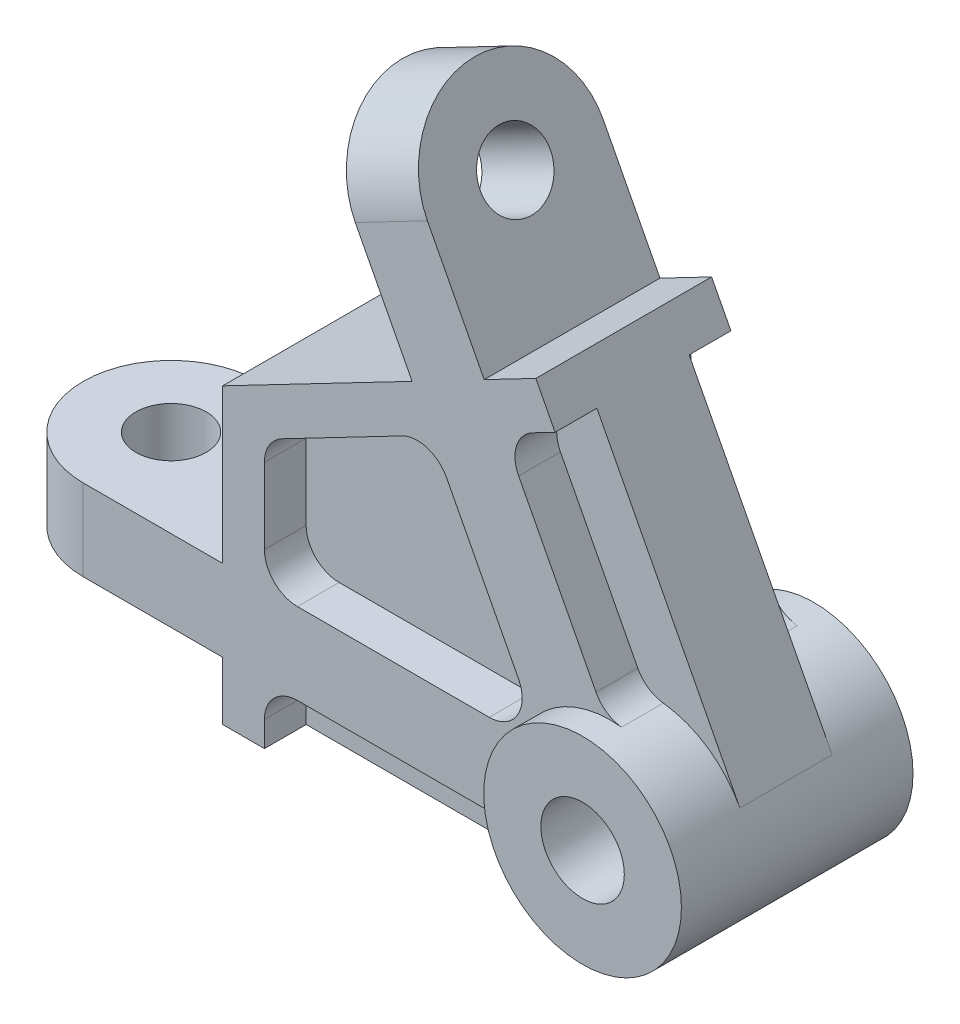
SolidWorks part; units mm, degrees
material "Alliage 1060"
ref_plane "Plan de face" through (0, 0, 0) normal (0, 0, 1) x (1, 0, 0)
ref_plane "Plan de dessus" through (0, 0, 0) normal (0, 1, 0) x (1, 0, 0)
ref_plane "Plan de droite" through (0, 0, 0) normal (1, 0, 0) x (0, 0, -1)
sketch "Esquisse2" plane through (0, 0, 0) normal (0, 0, 1) x (1, 0, 0)
  line L0 (0, 0) -> (88.25, 0)
  line L1 (71.2681, 103.8498) -> (108.2077, 32.8893)
  line L2 (71.2681, 103.8498) -> (59.5152, 97.7316)
  line L3 (59.5152, 97.7316) -> (46.586, 122.5683)
  line L4 (46.586, 122.5683) -> (30.1763, 114.026)
  line L5 (30.1763, 114.026) -> (43.1055, 89.1893)
  line L6 (43.1055, 89.1893) -> (0, 66.75)
  line L7 (0, 66.75) -> (0, 31.75)
  line L8 (0, 31.75) -> (-31.75, 31.75)
  line L9 (-31.75, 31.75) -> (-31.75, 13.25)
  line L10 (-31.75, 13.25) -> (0, 13.25)
  line L11 (0, 13.25) -> (0, 0)
  line L12 (88.25, 22.5) -> (-67.9696, 22.5) construction
  line L13 (88.25, 22.5) -> (6.9963, 178.5869) construction
  arc A0 (108.2077, 32.8893) -> (88.25, 0) centre (88.25, 22.5) ccw
  dimension "D1" = 45
  dimension "D3" = 108
  dimension "D4" = 120
  dimension "D5" = 31.75
  dimension "D6" = 35
  dimension "D7" = 18.5
  dimension "D8" = 18.5
  dimension "D9" = 9.25
  dimension "D10" = 62.5
  dimension "D11" = 9.25
extrude "Boss.-Extru.1" add sketch "Esquisse2" along normal mid plane 40
sketch "Esquisse4" plane through (0, 0, 0) normal (0, 0, 1) x (1, 0, 0)
  line L0 (-31.75, 31.75) -> (-31.75, 13.25) construction
  line L1 (46.586, 122.5683) -> (30.1763, 114.026) construction
  circle A0 centre (88.25, 22.5) radius 22.5
  dimension "D1" = 45
  dimension "D3" = 108
  dimension "D2" = 120
extrude "Boss.-Extru.2" add sketch "Esquisse4" along normal mid plane 52.7
sketch "Esquisse6" plane through (0, 0, 26.35) normal (0, 0, 1) x (1, 0, 0)
  circle A0 centre (88.25, 22.5) radius 9.5
  dimension "D1" = 19
extrude "Enlèv. mat.-Extru.1" cut sketch "Esquisse6" against normal through all
sketch "Esquisse7" plane through (0, 0, 20) normal (0, 0, 1) x (1, 0, 0)
  line L0 (9.5, 0) -> (9.5, 13.25)
  line L1 (0, 0) -> (88.25, 0) construction
  line L2 (9.5, 13.25) -> (63.3615, 13.25)
  line L3 (0, 13.25) -> (0, 0) construction
  line L4 (-31.75, 13.25) -> (0, 13.25) construction
  line L5 (9.5, 0) -> (88.25, 0)
  arc A0 (69.5836, 9.9375) -> (88.25, 0) centre (88.25, 22.5) ccw
  arc A2 (63.3615, 13.25) -> (69.5836, 9.9375) centre (63.3615, 5.75) cw
  circle A11 centre (88.25, 22.5) radius 22.5 construction
  arc A12 (108.2077, 32.8893) -> (88.25, 0) centre (88.25, 22.5) ccw construction
  dimension "D2" = 7.5
  dimension "D1" = 9.5
extrude "Enlèv. mat.-Extru.2" cut sketch "Esquisse7" against normal blind 9.5
fillet "Congé1" radius 7.5 1 edges at (9.5, 13.25, 15.25)
sketch "Esquisse11" plane through (0, 0, 20) normal (0, 0, 1) x (1, 0, 0)
  line L0 (47.4921, 80.7627) -> (67.2994, 42.7131)
  line L1 (30.1763, 114.026) -> (43.1055, 89.1893) construction
  line L2 (63.9018, 89.305) -> (84.9626, 48.8475)
  line L3 (59.5152, 97.7316) -> (46.586, 122.5683) construction
  line L4 (47.4921, 80.7627) -> (9.5, 60.9853)
  line L7 (9.5, 31.75) -> (60.6469, 31.75)
  line L8 (0, 31.75) -> (-31.75, 31.75) construction
  line L9 (9.5, 31.75) -> (9.5, 60.9853)
  line L10 (43.1055, 89.1893) -> (0, 66.75) construction
  line L11 (0, 66.75) -> (0, 31.75) construction
  line L12 (63.9018, 89.305) -> (75.6547, 95.4232)
  line L13 (108.2077, 32.8893) -> (71.2681, 103.8498) construction
  line L14 (71.2681, 103.8498) -> (59.5152, 97.7316) construction
  line L15 (108.2077, 32.8893) -> (75.6547, 95.4232)
  arc A1 (84.9626, 48.8475) -> (90.7739, 44.858) centre (91.6152, 52.3107) ccw
  arc A2 (108.2077, 32.8893) -> (69.5836, 9.9375) centre (88.25, 22.5) ccw construction
  arc A4 (108.2077, 32.8893) -> (90.7739, 44.858) centre (88.25, 22.5) ccw
  arc A5 (67.2994, 42.7131) -> (60.6469, 31.75) centre (60.6469, 39.25) cw
  dimension "D3" = 7.5
  dimension "D4" = 7.5
  dimension "D1" = 9.5
  dimension "D2" = 9.5
  dimension "D5" = 9.5
sketch "Esquisse18" plane through (0, 0, -20) normal (0, 0, -1) x (-1, 0, 0)
  line L0 (-9.5, 0) -> (-88.25, 0) construction
  line L1 (-9.5, 0) -> (-9.5, 13.25) construction
  line L2 (-9.5, 13.25) -> (-63.3615, 13.25) construction
  line L3 (-9.5, 0) -> (-88.25, 0)
  line L4 (-9.5, 0) -> (-9.5, 13.25)
  line L5 (-9.5, 13.25) -> (-63.3615, 13.25)
  arc A0 (-88.25, 0) -> (-69.5836, 9.9375) centre (-88.25, 22.5) ccw construction
  arc A1 (-63.3615, 13.25) -> (-69.5836, 9.9375) centre (-63.3615, 5.75) ccw construction
  arc A2 (-88.25, 0) -> (-69.5836, 9.9375) centre (-88.25, 22.5) ccw
  arc A3 (-63.3615, 13.25) -> (-69.5836, 9.9375) centre (-63.3615, 5.75) ccw
extrude "Enlèv. mat.-Extru.10" cut sketch "Esquisse18" against normal blind 9.5
extrude "Enlèv. mat.-Extru.6" cut sketch "Esquisse11" against normal blind 9.5
fillet "Congé3" radius 7.5 4 edges at (63.9018, 89.305, 15.25) (9.5, 31.75, 15.25) (9.5, 60.9853, 15.25) (47.4921, 80.7627, 15.25)
sketch "Esquisse12" plane through (0, 0, -20) normal (0, 0, -1) x (-1, 0, 0)
  line L3 (-75.6547, 95.4232) -> (-108.2077, 32.8893)
  line L4 (-84.9626, 48.8475) -> (-63.9018, 89.305)
  line L5 (-63.9018, 89.305) -> (-75.6547, 95.4232)
  line L6 (-75.6547, 95.4232) -> (-108.2077, 32.8893)
  line L7 (-84.9626, 48.8475) -> (-63.9018, 89.305)
  line L8 (-63.9018, 89.305) -> (-75.6547, 95.4232)
  line L10 (-9.5, 31.75) -> (-9.5, 60.9853)
  line L11 (-60.6469, 31.75) -> (-9.5, 31.75)
  line L12 (-47.4921, 80.7627) -> (-67.2994, 42.7131)
  line L13 (-9.5, 60.9853) -> (-47.4921, 80.7627)
  line L14 (-9.5, 31.75) -> (-9.5, 60.9853)
  line L15 (-60.6469, 31.75) -> (-9.5, 31.75)
  line L16 (-47.4921, 80.7627) -> (-67.2994, 42.7131)
  line L17 (-9.5, 60.9853) -> (-47.4921, 80.7627)
  arc A1 (-67.2994, 42.7131) -> (-60.6469, 31.75) centre (-60.6469, 39.25) ccw
  arc A2 (-90.7739, 44.858) -> (-108.2077, 32.8893) centre (-88.25, 22.5) ccw
  arc A3 (-90.7739, 44.858) -> (-84.9626, 48.8475) centre (-91.6152, 52.3107) ccw
  arc A4 (-90.7739, 44.858) -> (-108.2077, 32.8893) centre (-88.25, 22.5) ccw
  arc A5 (-90.7739, 44.858) -> (-84.9626, 48.8475) centre (-91.6152, 52.3107) ccw
  arc A6 (-67.2994, 42.7131) -> (-60.6469, 31.75) centre (-60.6469, 39.25) ccw
  dimension "D1" = 0
  dimension "D2" = 0
extrude "Enlèv. mat.-Extru.7" cut sketch "Esquisse12" against normal blind 9.5
fillet "Congé4" radius 7.5 4 edges at (9.5, 31.75, -15.25) (9.5, 60.9853, -15.25) (47.4921, 80.7627, -15.25) (63.9018, 89.305, -15.25)
sketch "Esquisse13" plane through (0, 31.75, 0) normal (0, 1, 0) x (1, 0, 0)
  line L0 (-31.75, -20) -> (-31.75, 20) construction
  line L1 (-31.75, -20) -> (-31.75, 20)
  arc A0 (-31.75, 20) -> (-31.75, -20) centre (-31.75, 0) ccw
extrude "Boss.-Extru.4" add sketch "Esquisse13" against normal blind 18.5
sketch "Esquisse14" plane through (0, 31.75, 0) normal (0, 1, 0) x (1, 0, 0)
  circle A0 centre (-31.75, 0) radius 8
  dimension "D1" = 16
extrude "Enlèv. mat.-Extru.8" cut sketch "Esquisse14" against normal through all
sketch "Esquisse15" plane through (86.8544, 45.2135, 0) normal (0.887, 0.4617, 0) x (0, 0, -1)
  line L0 (-20, 87.2084) -> (20, 87.2084) construction
  line L1 (-20, 87.2084) -> (20, 87.2084)
  arc A0 (20, 87.2084) -> (-20, 87.2084) centre (0, 87.2084) ccw
extrude "Boss.-Extru.5" add sketch "Esquisse15" against normal blind 18.5
sketch "Esquisse16" plane through (86.8544, 45.2135, 0) normal (0.887, 0.4617, 0) x (0, 0, -1)
  circle A0 centre (0, 87.2084) radius 8
  dimension "D1" = 16
extrude "Enlèv. mat.-Extru.9" cut sketch "Esquisse16" against normal through all
equation "\"A\" = 108mm"
equation "\"B\" = 18.50mm"
equation "\"C\" = 62.50"
equation "\"D3@Esquisse2\"=\"A\""
equation "\"D7@Esquisse2\"=\"B\""
equation "\"D8@Esquisse2\"=\"B\""
equation "\"D9@Esquisse2\"=\"B\"/2"
equation "\"D10@Esquisse2\"=\"C\""
equation "\"D11@Esquisse2\"=\"B\"/2"
equation "\"D3@Esquisse4\"=\"A\""
equation "\"D1@Boss.-Extru.4\"=\"B\""
equation "\"D1@Boss.-Extru.5\"=\"B\""
